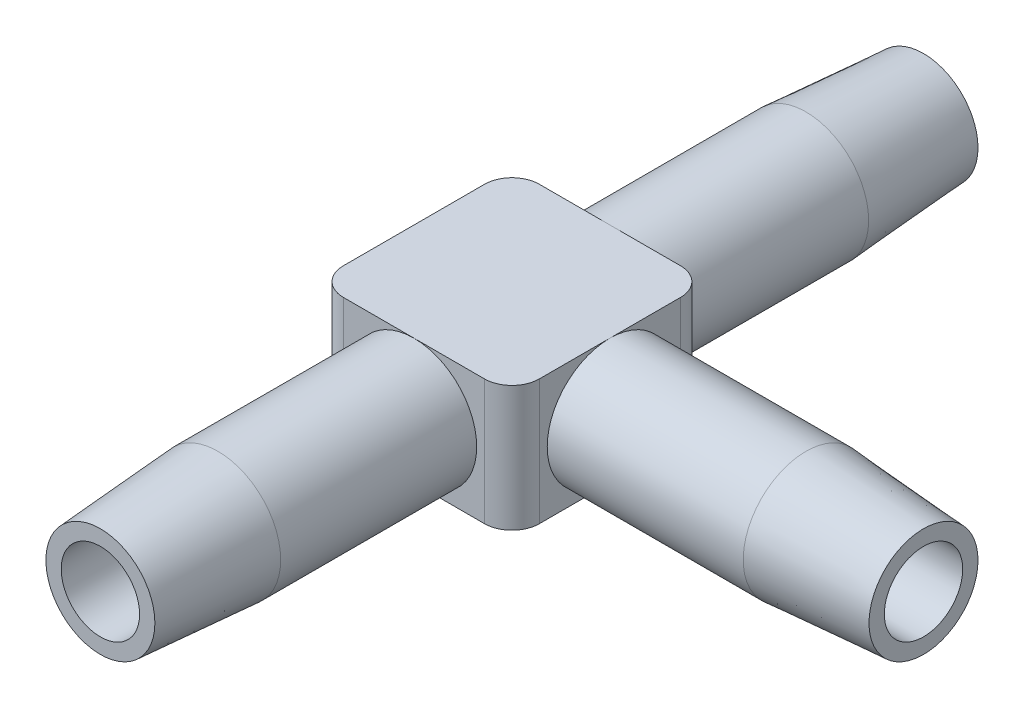
SolidWorks part; units mm, degrees
ref_plane "Front Plane" through (0, 0, 0) normal (0, 0, 1) x (1, 0, 0)
ref_plane "Top Plane" through (0, 0, 0) normal (0, 1, 0) x (1, 0, 0)
ref_plane "Right Plane" through (0, 0, 0) normal (1, 0, 0) x (0, 0, -1)
sketch "Sketch1" plane through (0, 0, 0) normal (0, 1, 0) x (1, 0, 0)
  line L1 (-5, 5) -> (5, 5)
  line L2 (-5, 5) -> (-5, -5)
  line L3 (-5, -5) -> (5, -5)
  line L4 (5, 5) -> (5, -5)
  point P4 (0, 5)
  point P6 (5, 0)
  dimension "D1" = 10
  dimension "D2" = 10
extrude "Boss-Extrude1" add sketch "Sketch1" along normal blind 6.4
sketch "Sketch2" plane through (0, 0, 5) normal (0, 0, 1) x (1, 0, 0)
  line L0 (-5, 6.4) -> (-5, 0) construction
  circle A0 centre (0, 3.2) radius 3.2
  point P2 (0, 0)
  point P3 (0, 0)
  point P5 (0, 0)
  point P8 (-5, 3.2)
  dimension "D1" = 6.4
extrude "Boss-Extrude2" add sketch "Sketch2" along normal blind 10
sketch "Sketch4" plane through (5, 0, 0) normal (1, 0, 0) x (0, 0, -1)
  line L0 (-5, 6.4) -> (-5, 0) construction
  circle A0 centre (0, 3.2) radius 3.2
  point P2 (0, 0)
  point P4 (0, 0)
  point P7 (-5, 3.2)
  dimension "D1" = 6.4
extrude "Boss-Extrude3" add sketch "Sketch4" along normal blind 10
sketch "Sketch8" plane through (15, 0, 0) normal (1, 0, 0) x (0, 0, -1)
  circle A2 centre (0, 3.2) radius 3.2
  dimension "D1" = 6.4
extrude "Boss-Extrude4" add sketch "Sketch8" along normal blind 6 draft 4
sketch "Sketch10" plane through (0, 0, 15) normal (0, 0, 1) x (1, 0, 0)
  circle A0 centre (0, 3.2) radius 3.2
  dimension "D1" = 6.4
extrude "Boss-Extrude5" add sketch "Sketch10" along normal blind 6 draft 4
mirror "Mirror2" about plane through (0, 0, 0) normal (0, 0, 1) of "Boss-Extrude5", "Boss-Extrude2"
fillet "Fillet1" radius 1.4 4 edges at (-5, 3.2, 5) (-5, 3.2, -5) (5, 3.2, -5) (5, 3.2, 5)
sketch "Sketch11" plane through (0, 0, 21) normal (0, 0, 1) x (1, 0, 0)
  circle A0 centre (0, 3.2) radius 2
  dimension "D1" = 4
extrude "Cut-Extrude5" cut sketch "Sketch11" against normal through all
sketch "Sketch9" plane through (21, 0, 0) normal (1, 0, 0) x (0, 0, -1)
  circle A0 centre (0, 3.2) radius 2
  dimension "D1" = 4
extrude "Cut-Extrude6" cut sketch "Sketch9" against normal up to next
